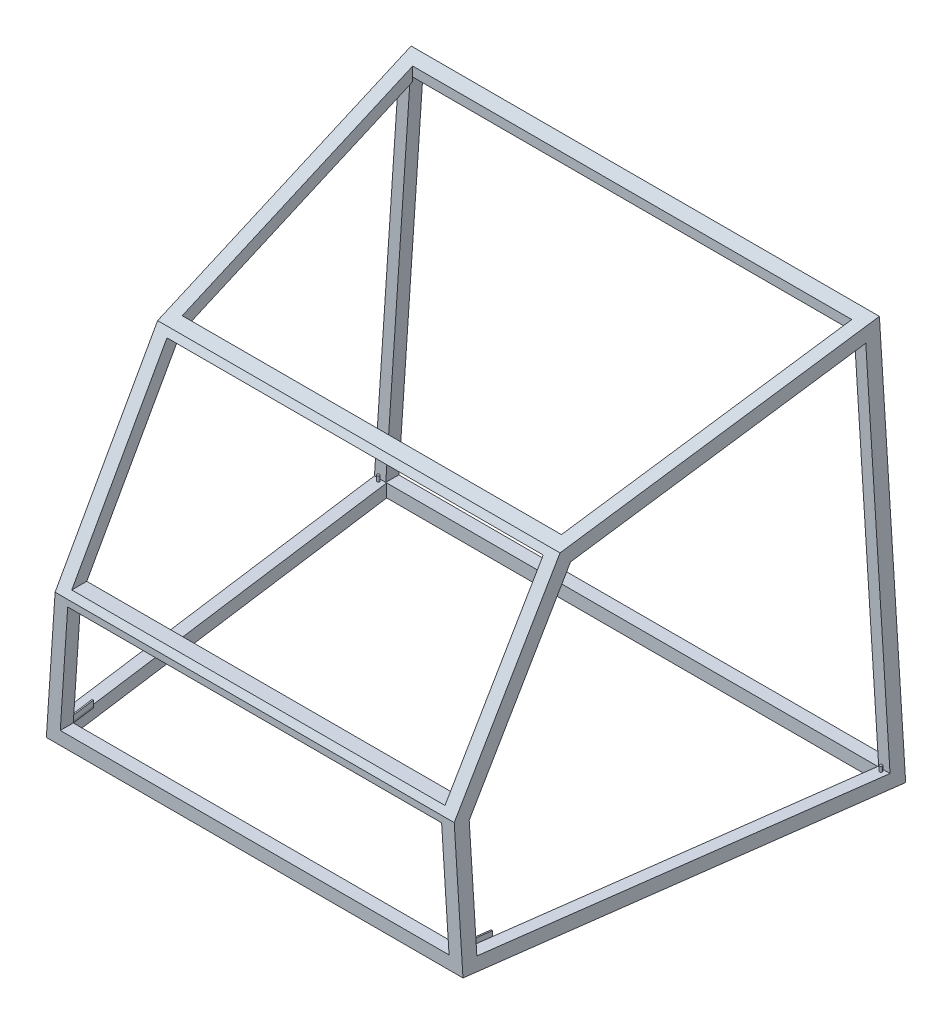
SolidWorks part; units mm, degrees
other "Marquage1"
sketch "Esquisse16" plane through (2000, 901.1413, 880.4452) normal (0.0577, 0.9108, 0.4088) x (0.9902, 0, -0.1397)
material "Thornel Mat VMA"
ref_plane "Plan de face" through (0, 0, 0) normal (0, 0, 1) x (1, 0, 0)
ref_plane "Plan de dessus" through (0, 0, 0) normal (0, 1, 0) x (1, 0, 0)
ref_plane "Plan de droite" through (0, 0, 0) normal (1, 0, 0) x (0, 0, -1)
sketch "Esquisse1" plane through (0, 0, 0) normal (1, 0, 0) x (0, 0, -1)
  line L0 (-880.4452, -98.8587) -> (-480.4452, 601.1413)
  line L1 (-480.4452, 601.1413) -> (619.5548, 901.1413)
  line L2 (619.5548, 901.1413) -> (619.5548, -598.8587)
  line L3 (619.5548, -598.8587) -> (-880.4452, -598.8587)
  line L4 (-880.4452, -598.8587) -> (-880.4452, -98.8587)
  dimension "D1" = 1500
  dimension "D2" = 1500
  dimension "D3" = 500
  dimension "D4" = 700
  dimension "D5" = 400
extrude "Boss.-Extru.1" add sketch "Esquisse1" along normal blind 2000
sketch "Esquisse2" plane through (0, -598.8587, 0) normal (0, -1, 0) x (1, 0, 0)
  line L0 (2000, -619.5548) -> (1800, 880.4452)
  line L1 (2000, 880.4452) -> (0, 880.4452) construction
  line L2 (1800, 880.4452) -> (2000, 880.4452)
  line L3 (2000, 880.4452) -> (2000, -619.5548)
  line L4 (1000, 880.4452) -> (1000, -619.5548) construction
  line L5 (2000, -619.5548) -> (0, -619.5548) construction
  line L6 (200, 880.4452) -> (0, 880.4452)
  line L7 (0, -619.5548) -> (200, 880.4452)
  line L8 (0, 880.4452) -> (0, -619.5548)
  dimension "D1" = 200
extrude "Enlèv. mat.-Extru.1" cut sketch "Esquisse2" against normal blind 2000
ref_plane "Plan1" through (116.0989, 0, -870.7417) normal (0.1322, 0, -0.9912) x (0, 1, 0)
sketch "Esquisse4" plane through (116.0989, 0, -870.7417) normal (0.1322, 0, -0.9912) x (0, 1, 0)
  line L0 (-598.8587, 1900.5731) -> (901.1413, 1900.5731)
  line L1 (901.1413, 1900.5731) -> (901.1413, 1800.5731)
  line L2 (901.1413, 1900.5731) -> (901.1413, -81.8827) construction
  line L3 (901.1413, 1800.5731) -> (-598.8587, 1900.5731)
  dimension "D1" = 100
extrude "Enlèv. mat.-Extru.2" cut sketch "Esquisse4" against normal blind 2000
ref_plane "Plan2" through (-81.1644, 0, -608.7329) normal (0.1322, 0, 0.9912) x (0, 1, 0)
sketch "Esquisse5" plane through (-81.1644, 0, -608.7329) normal (0.1322, 0, 0.9912) x (0, 1, 0)
  line L0 (901.1413, -81.8827) -> (-598.8587, -81.8827)
  line L3 (901.1413, -81.8827) -> (901.1413, -181.8827)
  line L4 (901.1413, -181.8827) -> (-598.8587, -81.8827)
  dimension "D1" = 100
extrude "Enlèv. mat.-Extru.3" cut sketch "Esquisse5" along normal blind 2000
sketch "Esquisse6" plane through (0, 0, 0) normal (1, 0, 0) x (0, 0, -1)
  line L0 (569.5548, 835.6788) -> (-447.3084, 558.3524)
  line L1 (-447.3084, 558.3524) -> (-830.4452, -112.1369)
  line L2 (-830.4452, -112.1369) -> (-830.4452, -548.8587)
  line L3 (-830.4452, -548.8587) -> (569.5548, -548.8587)
  line L4 (569.5548, -548.8587) -> (569.5548, 835.6788)
  line L6 (-480.4452, 601.1413) -> (619.5548, 901.1413) construction
  line L7 (619.5548, 901.1413) -> (619.5548, -598.8587) construction
  line L8 (-880.4452, -598.8587) -> (619.5548, -598.8587) construction
  line L9 (-880.4452, -598.8587) -> (-880.4452, -98.8587) construction
  line L10 (-880.4452, -98.8587) -> (-480.4452, 601.1413) construction
  dimension "D1" = 50
  dimension "D2" = 50
  dimension "D3" = 50
  dimension "D4" = 50
  dimension "D5" = 50
extrude "Enlèv. mat.-Extru.4" cut sketch "Esquisse6" along normal blind 2933
sketch "Esquisse7" plane through (0, 0, 0) normal (0, 0, 1) x (1, 0, 0)
  line L0 (282.0599, -123.8587) -> (253.4758, -548.8587)
  line L1 (253.4758, -548.8587) -> (1746.5242, -548.8587)
  line L2 (1746.5242, -548.8587) -> (1717.9401, -123.8587)
  line L3 (1717.9401, -123.8587) -> (282.0599, -123.8587)
  line L4 (283.407, -73.8587) -> (1716.593, -73.8587)
  line L5 (1716.593, -73.8587) -> (1722.4, 576.1413)
  line L6 (1722.4, 576.1413) -> (277.6, 576.1413)
  line L7 (277.6, 576.1413) -> (283.407, -73.8587)
  line L8 (176.2292, 851.1413) -> (271.0965, 626.1413)
  line L9 (271.0965, 626.1413) -> (1728.9035, 626.1413)
  line L10 (1728.9035, 626.1413) -> (1823.7708, 851.1413)
  line L11 (1823.7708, 851.1413) -> (176.2292, 851.1413)
  line L12 (200, -598.8587) -> (233.6283, -98.8587) construction
  line L13 (1766.3717, -98.8587) -> (233.6283, -98.8587) construction
  line L14 (1800, -598.8587) -> (200, -598.8587) construction
  line L16 (1800, -598.8587) -> (1766.3717, -98.8587) construction
  line L19 (227.3746, 601.1413) -> (100.885, 901.1413) construction
  line L20 (1772.6254, 601.1413) -> (1899.115, 901.1413) construction
  line L21 (1772.6254, 601.1413) -> (227.3746, 601.1413) construction
  line L22 (1899.115, 901.1413) -> (100.885, 901.1413) construction
  line L24 (1766.3717, -98.8587) -> (1772.6254, 601.1413) construction
  line L25 (233.6283, -98.8587) -> (227.3746, 601.1413) construction
  dimension "D1" = 50
  dimension "D2" = 25
  dimension "D3" = 25
  dimension "D4" = 50
  dimension "D5" = 50
  dimension "D6" = 50
  dimension "D7" = 50
  dimension "D8" = 25
  dimension "D9" = 25
  dimension "D10" = 50
  dimension "D11" = 50
  dimension "D12" = 50
extrude "Enlèv. mat.-Extru.5" cut sketch "Esquisse7" against normal blind 2933 and the other way blind 2933
sketch "Esquisse8" plane through (0, 0, -619.5548) normal (0, 0, -1) x (-1, 0, 0)
  line L0 (-1852.3649, 851.1413) -> (-1946.5242, -548.8587)
  line L1 (-1946.5242, -548.8587) -> (-53.4758, -548.8587)
  line L2 (-53.4758, -548.8587) -> (-147.6351, 851.1413)
  line L3 (-147.6351, 851.1413) -> (-1852.3649, 851.1413)
  line L4 (-1899.115, 901.1413) -> (-2000, -598.8587) construction
  line L5 (-100.885, 901.1413) -> (0, -598.8587) construction
  line L6 (-1899.115, 901.1413) -> (-100.885, 901.1413) construction
  line L7 (-2000, -598.8587) -> (0, -598.8587) construction
  dimension "D1" = 50
  dimension "D2" = 50
  dimension "D3" = 50
  dimension "D4" = 50
extrude "Enlèv. mat.-Extru.6" cut sketch "Esquisse8" against normal blind 50
sketch "Esquisse9" plane through (0, 0, 0) normal (0, 1, 0) x (1, 0, 0)
  line L0 (156.964, 569.5548) -> (271.9546, -430.4452)
  line L1 (271.9546, -430.4452) -> (1728.0454, -430.4452)
  line L2 (1728.0454, -430.4452) -> (1843.036, 569.5548)
  line L3 (1843.036, 569.5548) -> (156.964, 569.5548)
  line L4 (227.3746, -480.4452) -> (100.885, 619.5548) construction
  line L5 (1772.6254, -480.4452) -> (1899.115, 619.5548) construction
  line L6 (1899.115, 619.5548) -> (100.885, 619.5548) construction
  line L7 (1772.6254, -480.4452) -> (227.3746, -480.4452) construction
  dimension "D1" = 50
  dimension "D2" = 50
  dimension "D3" = 50
  dimension "D4" = 50
extrude "Enlèv. mat.-Extru.7" cut sketch "Esquisse9" along normal blind 1023
sketch "Esquisse10" plane through (0, -598.8587, 0) normal (0, -1, 0) x (1, 0, 0)
  line L0 (243.7758, 830.4452) -> (57.1092, -569.5548)
  line L1 (57.1092, -569.5548) -> (1942.8908, -569.5548)
  line L2 (1942.8908, -569.5548) -> (1756.2242, 830.4452)
  line L3 (1756.2242, 830.4452) -> (243.7758, 830.4452)
  line L4 (1800, 880.4452) -> (2000, -619.5548) construction
  line L5 (0, -619.5548) -> (200, 880.4452) construction
  line L6 (1800, 880.4452) -> (200, 880.4452) construction
  line L7 (2000, -619.5548) -> (0, -619.5548) construction
  dimension "D1" = 50
  dimension "D2" = 50
  dimension "D3" = 50
  dimension "D4" = 50
extrude "Enlèv. mat.-Extru.8" cut sketch "Esquisse10" against normal blind 50
sketch "Esquisse12" plane through (0, -548.8587, 0) normal (0, 1, 0) x (1, 0, 0)
  line L0 (1803.3038, -830.4452) -> (1989.9705, 569.5548) construction
  line L2 (1989.9705, 569.5548) -> (1896.8511, 569.5548) construction
  circle A0 centre (1965.0906, 559.5548) radius 5
  dimension "D3" = 10
  dimension "D1" = 23.34
  dimension "D2" = 10
sketch "Esquisse14" plane through (1834.3397, 0, 244.5786) normal (-0.9912, 0, -0.1322) x (-0.1322, 0, 0.9912)
  line L1 (591.0513, -548.8587) -> (496.4405, -548.8587)
  line L2 (591.0513, -548.8587) -> (591.0513, -552.7559)
  line L3 (591.0513, -552.7559) -> (496.4405, -552.7559)
  line L4 (496.4405, -548.8587) -> (496.4405, -552.7559)
extrude "Boss.-Extru.2" add sketch "Esquisse14" along normal blind 5
sketch "Esquisse15" plane through (0, -548.8587, 0) normal (0, 1, 0) x (1, 0, 0)
  line L4 (1768.7283, -736.6643) -> (1763.7722, -736.0035)
  line L8 (1763.7722, -736.0035) -> (1751.2038, -830.5638)
  line L9 (1751.2038, -830.5638) -> (1756.2242, -831.2311)
  line L10 (1756.2242, -831.2311) -> (1768.7283, -736.6643)
extrude "Boss.-Extru.28" add sketch "Esquisse15" along normal blind 20 and the other way blind 6
extrude "Boss.-Extru.29" add sketch "Esquisse12" along normal blind 20
ref_plane "Plan3" through (1000, 0, 0) normal (1, 0, 0) x (0, 0, -1)
mirror "Symétrie1" about plane through (1000, 0, 0) normal (1, 0, 0) of "Boss.-Extru.29", "Boss.-Extru.28", "Boss.-Extru.2"
